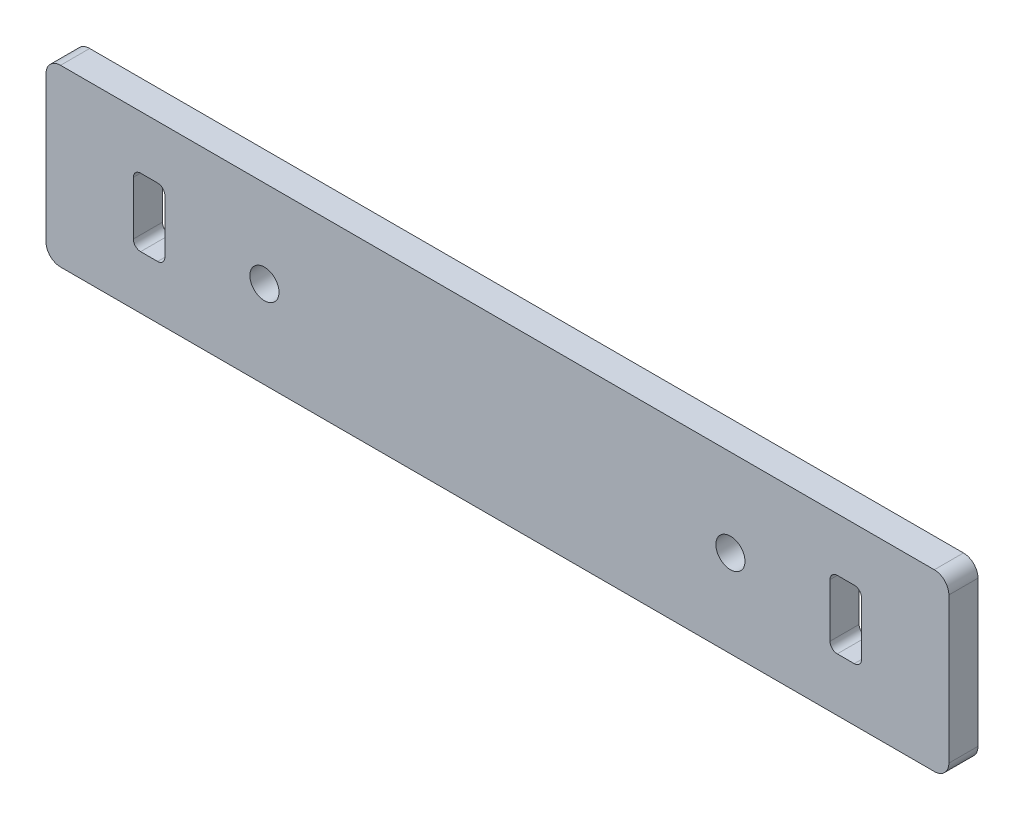
SolidWorks part; units mm, degrees
ref_plane "Alzado" through (0, 0, 0) normal (0, 0, 1) x (1, 0, 0)
ref_plane "Planta" through (0, 0, 0) normal (0, 1, 0) x (1, 0, 0)
ref_plane "Vista lateral" through (0, 0, 0) normal (1, 0, 0) x (0, 0, -1)
sketch "Model" plane through (0, 0, 0) normal (0, 0, 1) x (1, 0, 0)
  line L0 (-1478.2269, 336.9082) -> (-1388.2269, 336.9082)
  line L1 (-1478.2269, 318.9082) -> (-1388.2269, 318.9082)
  line L2 (-1469.9819, 331.4082) -> (-1468.2319, 331.4082)
  line L3 (-1468.2319, 324.4082) -> (-1469.9819, 324.4082)
  line L4 (-1470.7319, 325.1582) -> (-1470.7319, 330.6582)
  line L5 (-1467.4819, 325.1582) -> (-1467.4819, 330.6582)
  line L8 (-1398.2219, 331.4082) -> (-1396.4719, 331.4082)
  line L9 (-1396.4719, 324.4082) -> (-1398.2219, 324.4082)
  line L10 (-1398.9719, 325.1582) -> (-1398.9719, 330.6582)
  line L11 (-1395.7219, 325.1582) -> (-1395.7219, 330.6582)
  line L14 (-1479.7269, 320.4082) -> (-1479.7269, 335.4082)
  line L15 (-1386.7269, 320.4082) -> (-1386.7269, 335.4082)
  circle A0 centre (-1457.2269, 327.9082) radius 1.5
  circle A1 centre (-1409.2269, 327.9082) radius 1.5
  arc A2 (-1478.2269, 336.9082) -> (-1479.7269, 335.4082) centre (-1478.2269, 335.4082) ccw
  arc A3 (-1479.7269, 320.4082) -> (-1478.2269, 318.9082) centre (-1478.2269, 320.4082) ccw
  arc A4 (-1388.2269, 318.9082) -> (-1386.7269, 320.4082) centre (-1388.2269, 320.4082) ccw
  arc A5 (-1386.7269, 335.4082) -> (-1388.2269, 336.9082) centre (-1388.2269, 335.4082) ccw
  arc A6 (-1469.9819, 331.4082) -> (-1470.7319, 330.6582) centre (-1469.9819, 330.6582) ccw
  arc A7 (-1467.4819, 330.6582) -> (-1468.2319, 331.4082) centre (-1468.2319, 330.6582) ccw
  arc A8 (-1468.2319, 324.4082) -> (-1467.4819, 325.1582) centre (-1468.2319, 325.1582) ccw
  arc A9 (-1470.7319, 325.1582) -> (-1469.9819, 324.4082) centre (-1469.9819, 325.1582) ccw
  arc A10 (-1398.2219, 331.4082) -> (-1398.9719, 330.6582) centre (-1398.2219, 330.6582) ccw
  arc A11 (-1395.7219, 330.6582) -> (-1396.4719, 331.4082) centre (-1396.4719, 330.6582) ccw
  arc A12 (-1396.4719, 324.4082) -> (-1395.7219, 325.1582) centre (-1396.4719, 325.1582) ccw
  arc A13 (-1398.9719, 325.1582) -> (-1398.2219, 324.4082) centre (-1398.2219, 325.1582) ccw
extrude "Saliente-Extruir2" add sketch "Model" along normal blind 3
